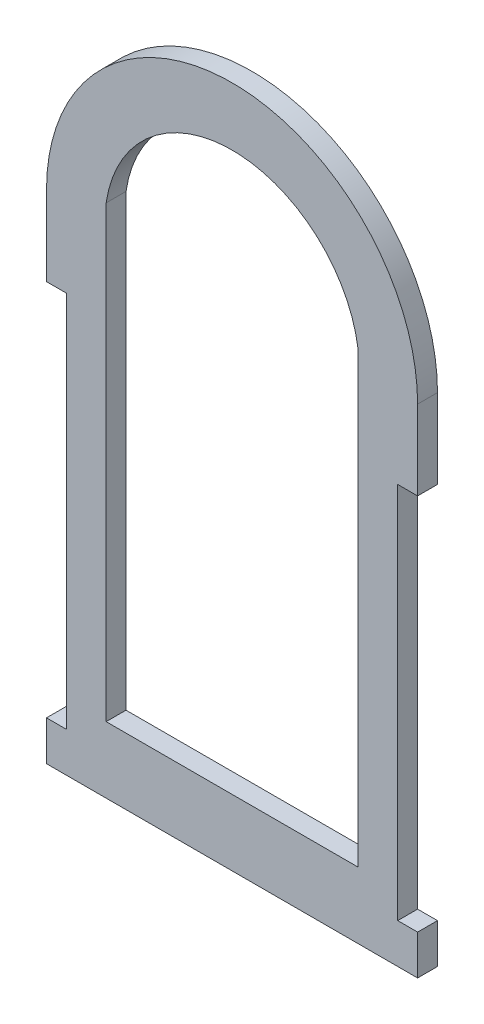
SolidWorks part; units mm, degrees
ref_plane "Front Plane" through (0, 0, 0) normal (0, 0, 1) x (1, 0, 0)
ref_plane "Top Plane" through (0, 0, 0) normal (0, 1, 0) x (1, 0, 0)
ref_plane "Right Plane" through (0, 0, 0) normal (1, 0, 0) x (0, 0, -1)
sketch "Sketch1" plane through (0, 0, 0) normal (0, 0, 1) x (1, 0, 0)
  line L0 (0, 0) -> (0, 102)
  line L1 (-28, 68) -> (28, 68)
  line L2 (28, 68) -> (28, 74)
  line L3 (-28, 68) -> (-28, 74)
  line L4 (28, 68) -> (28, 62)
  line L5 (28, 62) -> (25, 62)
  line L6 (25, 62) -> (25, 5)
  line L7 (25, 5) -> (28, 5)
  line L8 (28, 5) -> (28, -1)
  line L9 (28, -1) -> (19, -1)
  line L10 (19, -1) -> (19, 76.7955)
  line L11 (19, 76.7955) -> (19, 76.7955)
  line L12 (-19, 76.7955) -> (-19, 76.7955)
  line L13 (-19, 76.7955) -> (19, 76.7955) construction
  line L14 (-19, -1) -> (-19, 76.7955)
  line L15 (-28, -1) -> (-19, -1)
  line L16 (-28, 5) -> (-28, -1)
  line L17 (-25, 5) -> (-28, 5)
  line L18 (-25, 62) -> (-25, 5)
  line L19 (-28, 62) -> (-25, 62)
  line L20 (-28, 68) -> (-28, 62)
  line L21 (-28, 62) -> (-28, 68)
  line L22 (28, 62) -> (28, 68)
  line L23 (-19, -1) -> (19, -1)
  line L24 (-19, 5) -> (19, 5)
  arc A0 (-28, 74) -> (28, 74) centre (0, 74) cw
  arc A1 (-19, 76.7955) -> (19, 76.7955) centre (0, 74) cw
  point P6 (0, 68)
  dimension "D3" = 28
  dimension "D1" = 34
  dimension "D2" = 56
  dimension "D4" = 6
  dimension "D5" = 102
  dimension "D6" = 6
  dimension "D7" = 3
  dimension "D8" = 57
  dimension "D9" = 3
  dimension "D10" = 6
  dimension "D11" = 9
extrude "Boss-Extrude1" add sketch "Sketch1" along normal blind 3 contours L14 A1 L0 A0 L3 L1 | L0 A1 L10 L1 L2 A0 | L1 L20 L19 L18 L17 L16 L15 L14 | L10 L9 L8 L7 L6 L5 L4 L1
sketch "Sketch2" plane through (0, 0, 3) normal (0, 0, 1) x (1, 0, 0)
  line L0 (19, -1) -> (19, 76.7955) construction
  line L1 (-19, -1) -> (19, -1)
  line L2 (-19, -1) -> (-19, 9)
  line L3 (-19, 9) -> (19, 9)
  line L4 (19, -1) -> (19, 9)
  dimension "D1" = 10
extrude "Boss-Extrude2" add sketch "Sketch2" against normal blind 3
